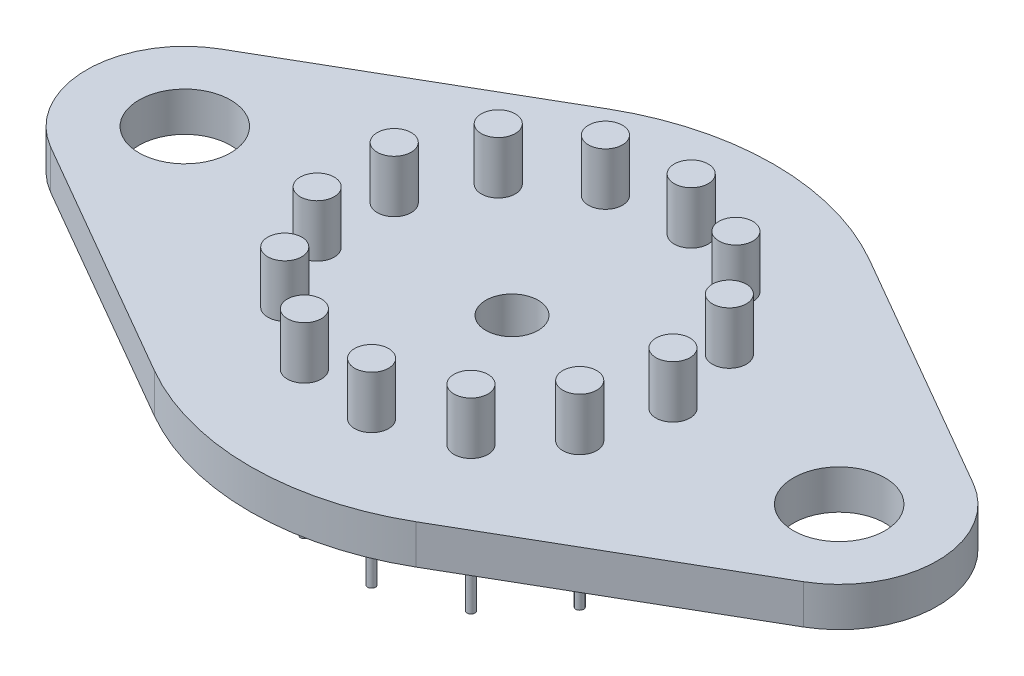
SolidWorks part; units mm, degrees
ref_plane "Plan de face" through (0, 0, 0) normal (0, 0, 1) x (1, 0, 0)
ref_plane "Plan de dessus" through (0, 0, 0) normal (0, 1, 0) x (1, 0, 0)
ref_plane "Plan de droite" through (0, 0, 0) normal (1, 0, 0) x (0, 0, -1)
sketch "Esquisse1" plane through (0, 0, 0) normal (0, 1, 0) x (1, 0, 0)
  line L0 (-12.5, 0) -> (12.5, 0) construction
  line L1 (-5, 8.6603) -> (-14.375, 3.2476)
  line L2 (-14.375, -3.2476) -> (-5, -8.6603)
  line L3 (5, 8.6603) -> (14.375, 3.2476)
  line L4 (5, -8.6603) -> (14.375, -3.2476)
  arc A0 (-5, -8.6603) -> (5, -8.6603) centre (0, 0) ccw
  arc A1 (-14.375, 3.2476) -> (-14.375, -3.2476) centre (-12.5, 0) ccw
  arc A2 (14.375, -3.2476) -> (14.375, 3.2476) centre (12.5, 0) ccw
  arc A3 (5, 8.6603) -> (-5, 8.6603) centre (0, 0) ccw
  point P9 (0, 0)
  dimension "D1" = 20
  dimension "D2" = 7.5
  dimension "D4" = 25
extrude "Boss.-Extru.1" add sketch "Esquisse1" along normal blind 1.5 contours L1 A1 L2 A0 L4 A2 L3 A3
sketch "Esquisse2" plane through (0, 1.5, 0) normal (0, 1, 0) x (1, 0, 0)
  line L0 (-12.5, 0) -> (12.5, 0) construction
  circle A0 centre (-12.5, 0) radius 1.75
  circle A1 centre (12.5, 0) radius 1.75
  point P4 (0, 0)
  dimension "D1" = 3.5
  dimension "D2" = 3.5
  dimension "D3" = 25
extrude "Enlèv. mat.-Extru.1" cut sketch "Esquisse2" against normal through all
sketch "Esquisse3" plane through (0, 1.5, 0) normal (0, 1, 0) x (1, 0, 0)
  circle A0 centre (6.15, 0) radius 0.65
  circle A1 centre (5.4456, -2.858) radius 0.65
  circle A2 centre (3.4936, -5.0614) radius 0.65
  circle A3 centre (0.7413, -6.1052) radius 0.65
  circle A4 centre (-2.1808, -5.7503) radius 0.65
  circle A5 centre (-4.6033, -4.0782) radius 0.65
  circle A6 centre (-5.9713, -1.4718) radius 0.65
  circle A7 centre (-5.9713, 1.4718) radius 0.65
  circle A8 centre (-4.6033, 4.0782) radius 0.65
  circle A9 centre (-2.1808, 5.7503) radius 0.65
  circle A10 centre (0.7413, 6.1052) radius 0.65
  circle A11 centre (3.4936, 5.0614) radius 0.65
  circle A12 centre (5.4456, 2.858) radius 0.65
  point P2 (6.15, 0)
  point P29 (0, 0)
  dimension "D1" = 1.3
  dimension "D2" = 6.15
  dimension "D3" = 13
extrude "Boss.-Extru.2" add sketch "Esquisse3" along normal blind 2
sketch "Esquisse4" plane through (0, 0, 0) normal (0, -1, 0) x (1, 0, 0)
  circle A0 centre (6.15, 0) radius 0.15
  circle A1 centre (5.4456, -2.858) radius 0.15
  circle A2 centre (3.4936, -5.0614) radius 0.15
  circle A3 centre (0.7413, -6.1052) radius 0.15
  circle A4 centre (-2.1808, -5.7503) radius 0.15
  circle A5 centre (-4.6033, -4.0782) radius 0.15
  circle A6 centre (-5.9713, -1.4718) radius 0.15
  circle A7 centre (-5.9713, 1.4718) radius 0.15
  circle A8 centre (-4.6033, 4.0782) radius 0.15
  circle A9 centre (-2.1808, 5.7503) radius 0.15
  circle A10 centre (0.7413, 6.1052) radius 0.15
  circle A11 centre (3.4936, 5.0614) radius 0.15
  circle A12 centre (5.4456, 2.858) radius 0.15
  point P2 (-6.15, 0)
  dimension "D1" = 0.3
  dimension "D2" = 6.15
  dimension "D3" = 13
extrude "Boss.-Extru.3" add sketch "Esquisse4" along normal blind 4
sketch "Esquisse6" plane through (0, 1.5, 0) normal (0, 1, 0) x (1, 0, 0)
  circle A0 centre (0, 0) radius 1
  dimension "D1" = 2
extrude "Enlèv. mat.-Extru.2" cut sketch "Esquisse6" against normal through all contours A0
